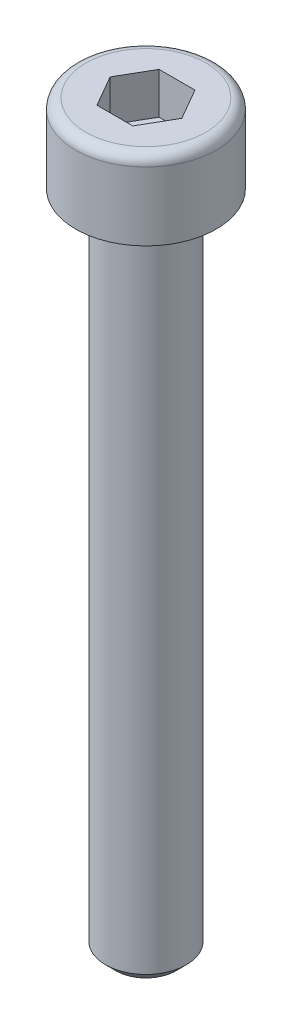
SolidWorks part; units mm, degrees
material "1023 Tôle d'acier au carbone (SS)"
ref_plane "Plan de face" through (0, 0, 0) normal (0, 0, 1) x (1, 0, 0)
ref_plane "Plan de dessus" through (0, 0, 0) normal (0, 1, 0) x (1, 0, 0)
ref_plane "Plan de droite" through (0, 0, 0) normal (1, 0, 0) x (0, 0, -1)
sketch "Esquisse1" plane through (0, 0, 0) normal (0, 0, 1) x (1, 0, 0)
  line L0 (0, 3.8) -> (0, -32) construction
  line L1 (0, 3.8) -> (-2.9, 3.8)
  line L2 (-3.4, 3.3) -> (-3.4, 0)
  line L3 (-3.4, 0) -> (-1.95, 0)
  line L4 (-1.95, 0) -> (-1.95, -31.5)
  line L5 (-1.95, -31.5) -> (-1.45, -32)
  line L6 (-1.45, -32) -> (0, -32)
  line L7 (0, 3.8) -> (0, -32)
  arc A0 (-2.9, 3.8) -> (-3.4, 3.3) centre (-2.9, 3.3) ccw
  point P11 (-1.95, -32)
  dimension "D5" = 0.5
  dimension "D1" = 3.9
  dimension "D2" = 6.8
  dimension "D3" = 32
  dimension "D4" = 3.8
  dimension "D8" = 0.5
revolve "Révolution1" add sketch "Esquisse1" angle 360 about L0
cosmetic thread "Représentation de filetage1" parameters "D2"=3.2
sketch "Esquisse2" plane through (0, 3.8, 0) normal (0, 1, 0) x (-1, 0, 0)
  line L1 (-1.7321, 0) -> (-0.866, -1.5)
  line L2 (-0.866, -1.5) -> (0.866, -1.5)
  line L3 (0.866, -1.5) -> (1.7321, 0)
  line L4 (1.7321, 0) -> (0.866, 1.5)
  line L5 (0.866, 1.5) -> (-0.866, 1.5)
  line L6 (-0.866, 1.5) -> (-1.7321, 0)
  circle A0 centre (0, 0) radius 1.5 construction
  dimension "D1" = 3
extrude "Enlèv. mat.-Extru.1" cut sketch "Esquisse2" against normal blind 2
